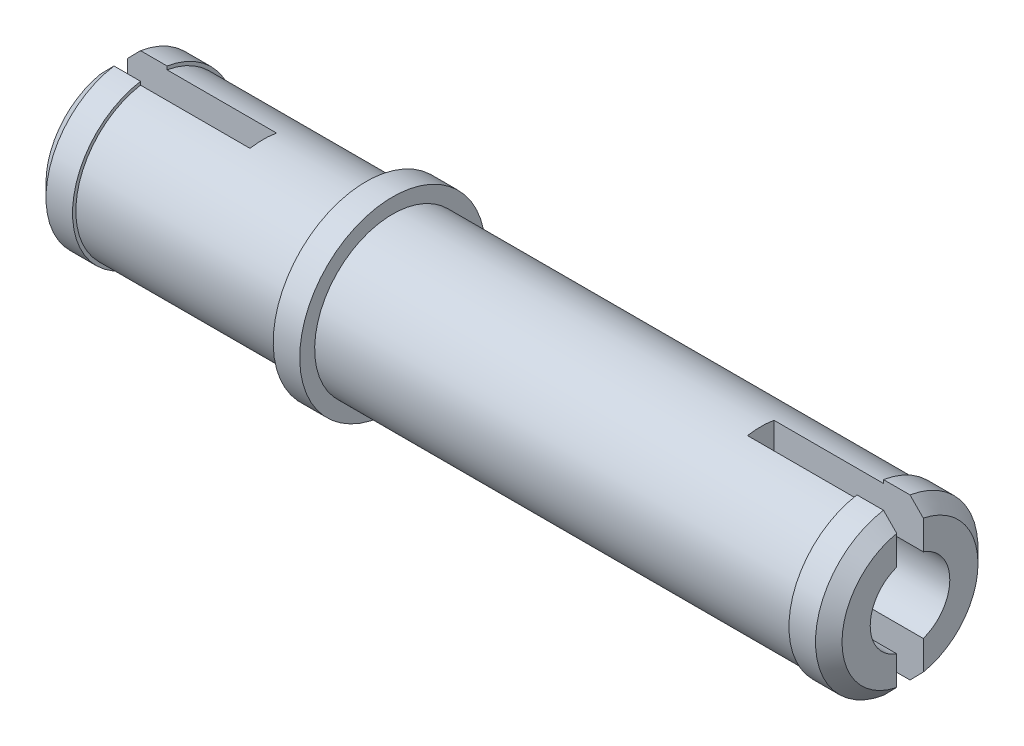
SolidWorks part; units mm, degrees
ref_plane "Front Plane" through (0, 0, 0) normal (0, 0, 1) x (1, 0, 0)
ref_plane "Top Plane" through (0, 0, 0) normal (0, 1, 0) x (1, 0, 0)
ref_plane "Right Plane" through (0, 0, 0) normal (1, 0, 0) x (0, 0, -1)
sketch "Sketch1" plane through (0, 0, 0) normal (0, 0, 1) x (1, 0, 0)
  line L0 (-12, 0) -> (12, 0)
  line L1 (-12, 0) -> (-12, 2.45)
  line L2 (-12, 2.45) -> (-10.8, 2.45)
  line L3 (-10.8, 2.45) -> (-10.8, 2.35)
  line L4 (-10.8, 2.35) -> (-4.4, 2.35)
  line L5 (-4.4, 2.35) -> (-4.4, 2.8)
  line L6 (-4.4, 2.8) -> (-3.6, 2.8)
  line L7 (-3.6, 2.8) -> (-3.6, 2.35)
  line L8 (-3.6, 2.35) -> (10.8, 2.35)
  line L9 (10.8, 2.35) -> (10.8, 2.45)
  line L10 (10.8, 2.45) -> (12, 2.45)
  line L11 (12, 2.45) -> (12, 0)
  line L12 (12, 0) -> (-12, 0) construction
  point P3 (8, 0)
  point P4 (0, 0)
  dimension "D1" = 24
  dimension "D2" = 2.45
  dimension "D3" = 1.2
  dimension "D4" = 0.1
  dimension "D5" = 6.4
  dimension "D6" = 0.45
  dimension "D7" = 0.8
  dimension "D8" = 14.4
revolve "Revolve1" add sketch "Sketch1" angle 360 about L0
sketch "Sketch2" plane through (0, 0, 0) normal (0, 1, 0) x (1, 0, 0)
  line L0 (-9.1343, 0) -> (9.1343, 0) construction
  line L1 (-12, 2.45) -> (-12, -2.45) construction
  line L2 (-14.8228, 0.4) -> (-7.5, 0.4)
  line L3 (-14.8228, 0.4) -> (-14.8228, -0.4)
  line L4 (-14.8228, -0.4) -> (-7.5, -0.4)
  line L5 (-7.5, 0.4) -> (-7.5, -0.4)
  line L6 (-14.8228, 0.4) -> (-7.5, -0.4) construction
  line L7 (-14.8228, -0.4) -> (-7.5, 0.4) construction
  line L8 (14.057, 0.4) -> (7.5, 0.4)
  line L9 (14.057, 0.4) -> (14.057, -0.4)
  line L10 (14.057, -0.4) -> (7.5, -0.4)
  line L11 (7.5, 0.4) -> (7.5, -0.4)
  line L12 (14.057, 0.4) -> (7.5, -0.4) construction
  line L13 (14.057, -0.4) -> (7.5, 0.4) construction
  line L14 (12, -2.45) -> (12, 2.45) construction
  point P0 (-11.1614, 0)
  point P4 (0, 0)
  point P10 (10.7785, 0)
  dimension "D1" = 0.8
  dimension "D2" = 4.5
  dimension "D3" = 0.8
  dimension "D4" = 4.5
extrude "Cut-Extrude1" cut sketch "Sketch2" against normal through all both and the other way through all
chamfer "Chamfer1" distance 0.4 angle 45 4 edges at (-12, 0, -2.45) (-12, 0, 2.45) (12, 0, -2.45) (12, 0, 2.45)
sketch "Sketch3" plane through (12, 0, 0) normal (1, 0, 0) x (0, 0, -1)
  circle A0 centre (0, 0) radius 1.2
  dimension "D1" = 2.4
extrude "Cut-Extrude2" cut sketch "Sketch3" against normal through all and the other way through all
